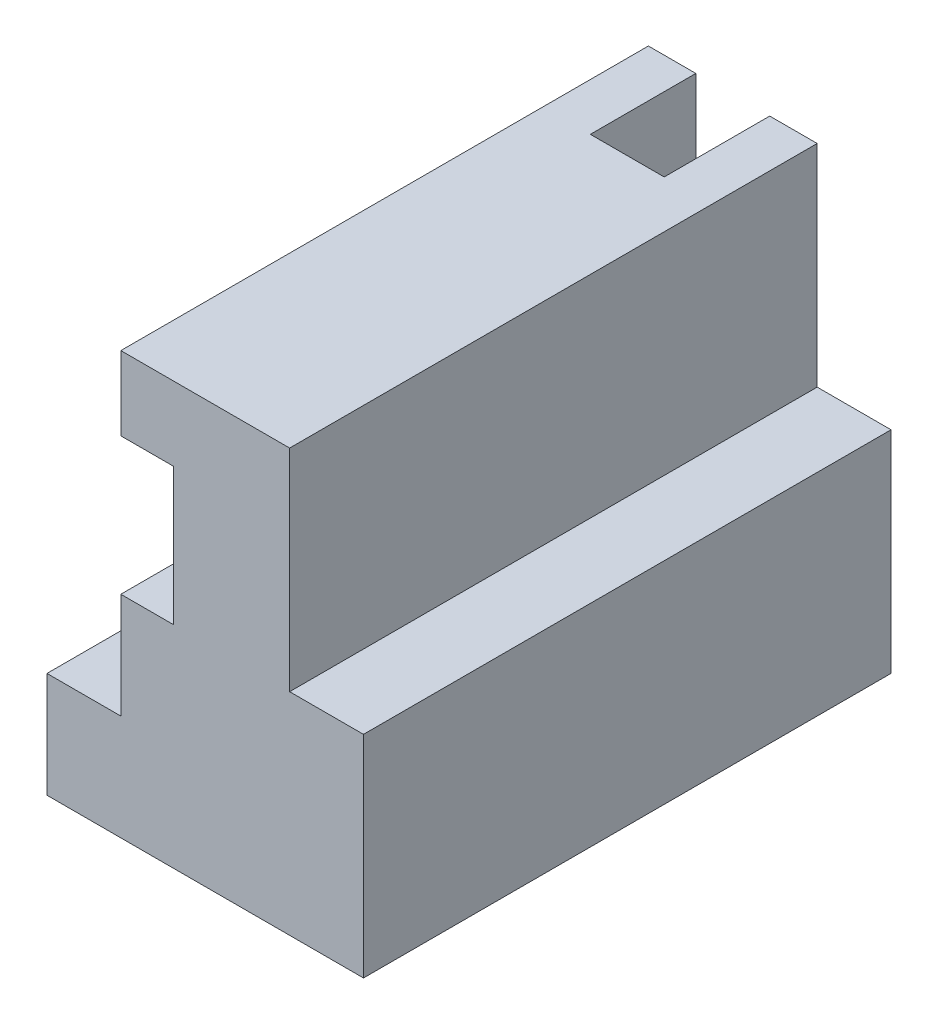
SolidWorks part; units mm, degrees
ref_plane "Спереди" through (0, 0, 0) normal (0, 0, 1) x (1, 0, 0)
ref_plane "Сверху" through (0, 0, 0) normal (0, 1, 0) x (1, 0, 0)
ref_plane "Справа" through (0, 0, 0) normal (1, 0, 0) x (0, 0, -1)
sketch "Эскиз1" plane through (0, 0, 0) normal (0, 0, 1) x (1, 0, 0)
  line L0 (-8, 20) -> (-8, -10)
  line L1 (-15, -20) -> (15, -20)
  line L2 (-15, -20) -> (-15, 20)
  line L3 (-15, 20) -> (15, 20)
  line L4 (15, -20) -> (15, 20)
  line L5 (-15, -20) -> (15, 20) construction
  line L6 (-15, 20) -> (15, -20) construction
  line L7 (-8, -10) -> (-15, -10)
  line L8 (8, 0) -> (15, 0)
  line L10 (8, 0) -> (8, 10)
  line L11 (8, 10) -> (8, 20)
  point P0 (0, 0)
  dimension "D1" = 30
  dimension "D2" = 40
  dimension "D3" = 7
  dimension "D4" = 30
  dimension "D5" = 7
  dimension "D8" = 30
extrude "Бобышка-Вытянуть2" add sketch "Эскиз1" along normal blind 50
sketch "Эскиз2" plane through (0, 0, 0) normal (0, 0, -1) x (-1, 0, 0)
  line L0 (0, -20) -> (0, 20) construction
  line L1 (15, -20) -> (-15, -20) construction
  line L2 (8, 20) -> (-8, 20) construction
  line L4 (-3.5, -20) -> (3.5, -20)
  line L5 (-3.5, -20) -> (-3.5, 20)
  line L6 (-3.5, 20) -> (3.5, 20)
  line L7 (3.5, -20) -> (3.5, 20)
  line L8 (-3.5, -20) -> (3.5, 20) construction
  line L9 (-3.5, 20) -> (3.5, -20) construction
  line L10 (-10, -20) -> (10, -20)
  line L11 (-10, -20) -> (-10, -15)
  line L12 (-10, -15) -> (10, -15)
  line L13 (10, -20) -> (10, -15)
  line L14 (-10, -20) -> (10, -15) construction
  line L15 (-10, -15) -> (10, -20) construction
  point P6 (0, 0)
  point P11 (0, -17.5)
  line M5 (-15, -20) -> (15, -20)
  line M9 (8, 20) -> (-8, 20)
  dimension "D1" = 7
  dimension "D2" = 20
  dimension "D3" = 5
extrude "Вырез-Вытянуть1" cut sketch "Эскиз2" against normal blind 10 contours L5 L12 L7 M9 | L12 L5 L7 M5 | L13 L12 L7 M5 | L12 L11 L5 M5
sketch "Эскиз3" plane through (-8, 0, 0) normal (-1, 0, 0) x (0, 0, 1)
  line L0 (50, 20) -> (50, -10) construction
  line L1 (50, 13) -> (42, 13)
  line L2 (50, 13) -> (50, 0)
  line L3 (50, 0) -> (42, 0)
  line L4 (42, 13) -> (42, 0)
  line L5 (50, 0) -> (0, 0) construction
  dimension "D1" = 13
  dimension "D2" = 8
extrude "Вырез-Вытянуть2" cut sketch "Эскиз3" against normal blind 5
